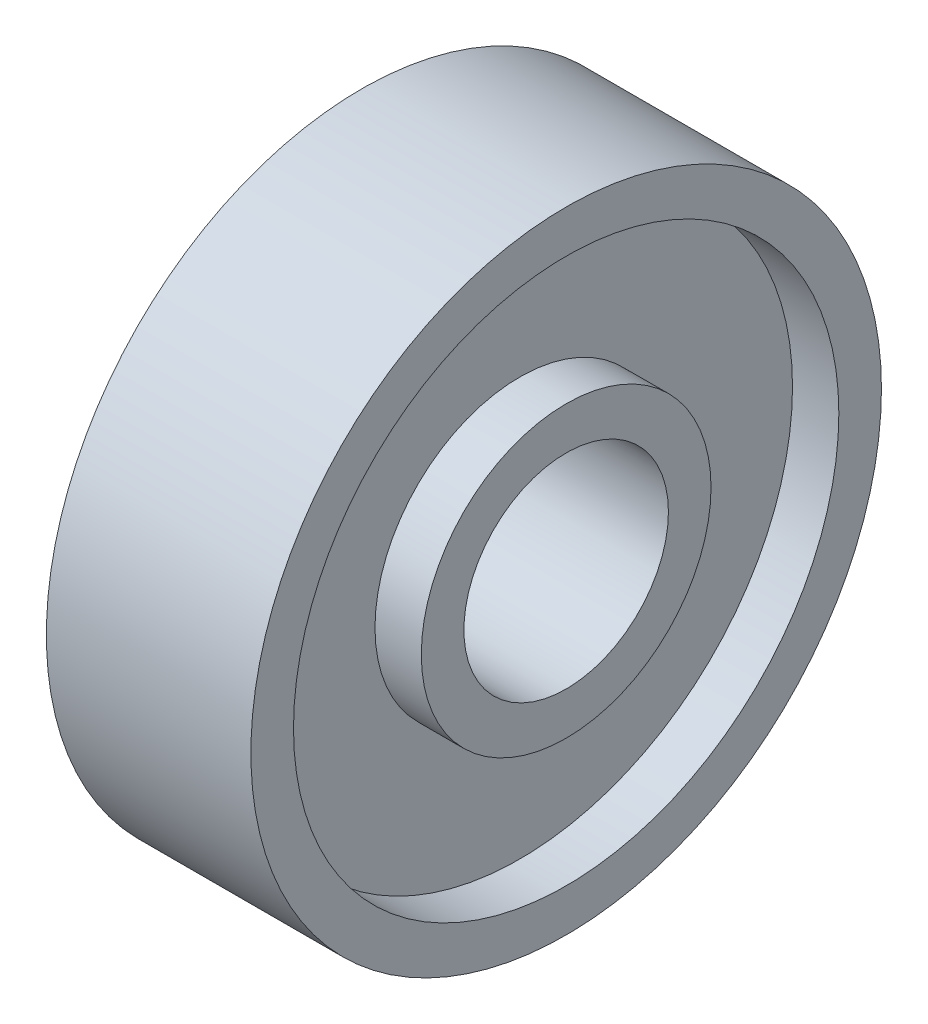
SolidWorks part; units mm, degrees
material "Plain Carbon Steel"
ref_plane "Front Plane" through (0, 0, 0) normal (0, 0, 1) x (1, 0, 0)
ref_plane "Top Plane" through (0, 0, 0) normal (0, 1, 0) x (1, 0, 0)
ref_plane "Right Plane" through (0, 0, 0) normal (1, 0, 0) x (0, 0, -1)
sketch "Sketch1" plane through (0, 0, 0) normal (1, 0, 0) x (0, 0, -1)
  circle A0 centre (0, 0) radius 18.5
  circle A1 centre (0, 0) radius 6
  dimension "D1" = 12
  dimension "D2" = 37
extrude "Boss-Extrude1" add sketch "Sketch1" along normal mid plane 12
sketch "Sketch2" plane through (0, 0, 0) normal (0, 0, 1) x (1, 0, 0)
  line L0 (3.2812, 16) -> (3.2812, 8.5)
  line L1 (3.2812, 16) -> (8.7188, 16)
  line L2 (3.2812, 8.5) -> (8.7188, 8.5)
  line L3 (8.7188, 16) -> (8.7188, 8.5)
  line L4 (3.2812, 16) -> (8.7188, 8.5) construction
  line L5 (3.2812, 8.5) -> (8.7188, 16) construction
  line L6 (-8.7188, 16) -> (-3.2812, 16)
  line L7 (-8.7188, 16) -> (-8.7188, 8.5)
  line L8 (-3.2812, 16) -> (-3.2812, 8.5)
  line L9 (-8.7188, 8.5) -> (-3.2812, 8.5)
  line L10 (-8.7188, 16) -> (-3.2812, 8.5) construction
  line L11 (-3.2812, 16) -> (-8.7188, 8.5) construction
  line L12 (0, 0) -> (17.9174, 0) construction
  line L13 (6, -18.5) -> (6, 18.5) construction
  line L14 (-6, 18.5) -> (-6, -18.5) construction
  point P1 (6, 12.25)
  point P2 (-6, 12.25)
  dimension "D1" = 17
  dimension "D2" = 32
revolve "Cut-Revolve1" cut sketch "Sketch2" angle 360 about L12
